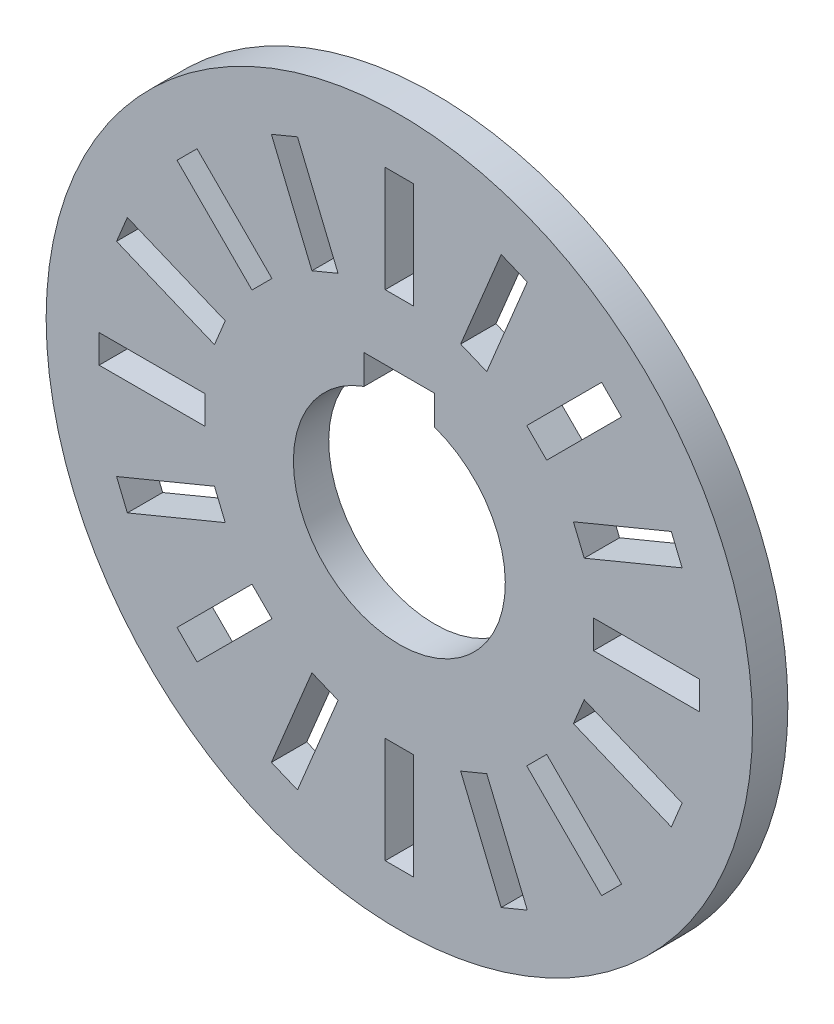
SolidWorks part; units mm, degrees
material "Malleable Cast Iron"
ref_plane "Front Plane" through (0, 0, 0) normal (0, 0, 1) x (1, 0, 0)
ref_plane "Top Plane" through (0, 0, 0) normal (0, 1, 0) x (1, 0, 0)
ref_plane "Right Plane" through (0, 0, 0) normal (1, 0, 0) x (0, 0, -1)
sketch "Sketch1" plane through (0, 0, 0) normal (0, 0, 1) x (1, 0, 0)
  line L0 (-5, 14.1421) -> (-5, 18.3)
  line L1 (5, 18.3) -> (5, 14.1421)
  line L2 (-5, 18.3) -> (5, 18.3)
  line L3 (0, 0) -> (0, 50) construction
  line L4 (-42.5, 2) -> (-27.5, 2)
  line L5 (-42.5, 2) -> (-42.5, -2)
  line L6 (-42.5, -2) -> (-27.5, -2)
  line L7 (-27.5, 2) -> (-27.5, -2)
  line L8 (-42.5, 2) -> (-27.5, -2) construction
  line L9 (-42.5, -2) -> (-27.5, 2) construction
  line L10 (0, 0) -> (19.1342, 46.194) construction
  line L11 (0, 0) -> (35.3553, 35.3553) construction
  line L12 (0, 0) -> (46.194, 19.1342) construction
  line L13 (0, 0) -> (50, 0) construction
  line L14 (0, 0) -> (46.194, -19.1342) construction
  line L15 (0, 0) -> (35.3553, -35.3553) construction
  line L16 (0, 0) -> (19.1342, -46.194) construction
  line L17 (0, 0) -> (0, -50) construction
  line L18 (0, 0) -> (-19.1342, -46.194) construction
  line L19 (0, 0) -> (-35.3553, -35.3553) construction
  line L20 (0, 0) -> (-46.194, -19.1342) construction
  line L21 (0, 0) -> (-50, 0) construction
  line L22 (0, 0) -> (-46.194, 19.1342) construction
  line L23 (0, 0) -> (-35.3553, 35.3553) construction
  line L24 (0, 0) -> (-19.1342, 46.194) construction
  line L25 (-38.4995, 18.1118) -> (-24.6413, 12.3716)
  line L26 (-38.4995, 18.1118) -> (-26.1721, 8.676) construction
  line L27 (-38.4995, 18.1118) -> (-40.0302, 14.4163)
  line L28 (-24.6413, 12.3716) -> (-26.1721, 8.676)
  line L29 (-40.0302, 14.4163) -> (-26.1721, 8.676)
  line L30 (-40.0302, 14.4163) -> (-24.6413, 12.3716) construction
  line L31 (-28.6378, 31.4663) -> (-18.0312, 20.8597)
  line L32 (-28.6378, 31.4663) -> (-20.8597, 18.0312) construction
  line L33 (-28.6378, 31.4663) -> (-31.4663, 28.6378)
  line L34 (-18.0312, 20.8597) -> (-20.8597, 18.0312)
  line L35 (-31.4663, 28.6378) -> (-20.8597, 18.0312)
  line L36 (-31.4663, 28.6378) -> (-18.0312, 20.8597) construction
  line L37 (-14.4163, 40.0302) -> (-8.676, 26.1721)
  line L38 (-14.4163, 40.0302) -> (-12.3716, 24.6413) construction
  line L39 (-14.4163, 40.0302) -> (-18.1118, 38.4995)
  line L40 (-8.676, 26.1721) -> (-12.3716, 24.6413)
  line L41 (-18.1118, 38.4995) -> (-12.3716, 24.6413)
  line L42 (-18.1118, 38.4995) -> (-8.676, 26.1721) construction
  line L43 (2, 42.5) -> (2, 27.5)
  line L44 (2, 42.5) -> (-2, 27.5) construction
  line L45 (2, 42.5) -> (-2, 42.5)
  line L46 (2, 27.5) -> (-2, 27.5)
  line L47 (-2, 42.5) -> (-2, 27.5)
  line L48 (-2, 42.5) -> (2, 27.5) construction
  line L49 (18.1118, 38.4995) -> (12.3716, 24.6413)
  line L50 (18.1118, 38.4995) -> (8.676, 26.1721) construction
  line L51 (18.1118, 38.4995) -> (14.4163, 40.0302)
  line L52 (12.3716, 24.6413) -> (8.676, 26.1721)
  line L53 (14.4163, 40.0302) -> (8.676, 26.1721)
  line L54 (14.4163, 40.0302) -> (12.3716, 24.6413) construction
  line L55 (31.4663, 28.6378) -> (20.8597, 18.0312)
  line L56 (31.4663, 28.6378) -> (18.0312, 20.8597) construction
  line L57 (31.4663, 28.6378) -> (28.6378, 31.4663)
  line L58 (20.8597, 18.0312) -> (18.0312, 20.8597)
  line L59 (28.6378, 31.4663) -> (18.0312, 20.8597)
  line L60 (28.6378, 31.4663) -> (20.8597, 18.0312) construction
  line L61 (40.0302, 14.4163) -> (26.1721, 8.676)
  line L62 (40.0302, 14.4163) -> (24.6413, 12.3716) construction
  line L63 (40.0302, 14.4163) -> (38.4995, 18.1118)
  line L64 (26.1721, 8.676) -> (24.6413, 12.3716)
  line L65 (38.4995, 18.1118) -> (24.6413, 12.3716)
  line L66 (38.4995, 18.1118) -> (26.1721, 8.676) construction
  line L67 (42.5, -2) -> (27.5, -2)
  line L68 (42.5, -2) -> (27.5, 2) construction
  line L69 (42.5, -2) -> (42.5, 2)
  line L70 (27.5, -2) -> (27.5, 2)
  line L71 (42.5, 2) -> (27.5, 2)
  line L72 (42.5, 2) -> (27.5, -2) construction
  line L73 (38.4995, -18.1118) -> (24.6413, -12.3716)
  line L74 (38.4995, -18.1118) -> (26.1721, -8.676) construction
  line L75 (38.4995, -18.1118) -> (40.0302, -14.4163)
  line L76 (24.6413, -12.3716) -> (26.1721, -8.676)
  line L77 (40.0302, -14.4163) -> (26.1721, -8.676)
  line L78 (40.0302, -14.4163) -> (24.6413, -12.3716) construction
  line L79 (28.6378, -31.4663) -> (18.0312, -20.8597)
  line L80 (28.6378, -31.4663) -> (20.8597, -18.0312) construction
  line L81 (28.6378, -31.4663) -> (31.4663, -28.6378)
  line L82 (18.0312, -20.8597) -> (20.8597, -18.0312)
  line L83 (31.4663, -28.6378) -> (20.8597, -18.0312)
  line L84 (31.4663, -28.6378) -> (18.0312, -20.8597) construction
  line L85 (14.4163, -40.0302) -> (8.676, -26.1721)
  line L86 (14.4163, -40.0302) -> (12.3716, -24.6413) construction
  line L87 (14.4163, -40.0302) -> (18.1118, -38.4995)
  line L88 (8.676, -26.1721) -> (12.3716, -24.6413)
  line L89 (18.1118, -38.4995) -> (12.3716, -24.6413)
  line L90 (18.1118, -38.4995) -> (8.676, -26.1721) construction
  line L91 (-2, -42.5) -> (-2, -27.5)
  line L92 (-2, -42.5) -> (2, -27.5) construction
  line L93 (-2, -42.5) -> (2, -42.5)
  line L94 (-2, -27.5) -> (2, -27.5)
  line L95 (2, -42.5) -> (2, -27.5)
  line L96 (2, -42.5) -> (-2, -27.5) construction
  line L97 (-18.1118, -38.4995) -> (-12.3716, -24.6413)
  line L98 (-18.1118, -38.4995) -> (-8.676, -26.1721) construction
  line L99 (-18.1118, -38.4995) -> (-14.4163, -40.0302)
  line L100 (-12.3716, -24.6413) -> (-8.676, -26.1721)
  line L101 (-14.4163, -40.0302) -> (-8.676, -26.1721)
  line L102 (-14.4163, -40.0302) -> (-12.3716, -24.6413) construction
  line L103 (-31.4663, -28.6378) -> (-20.8597, -18.0312)
  line L104 (-31.4663, -28.6378) -> (-18.0312, -20.8597) construction
  line L105 (-31.4663, -28.6378) -> (-28.6378, -31.4663)
  line L106 (-20.8597, -18.0312) -> (-18.0312, -20.8597)
  line L107 (-28.6378, -31.4663) -> (-18.0312, -20.8597)
  line L108 (-28.6378, -31.4663) -> (-20.8597, -18.0312) construction
  line L109 (-40.0302, -14.4163) -> (-26.1721, -8.676)
  line L110 (-40.0302, -14.4163) -> (-24.6413, -12.3716) construction
  line L111 (-40.0302, -14.4163) -> (-38.4995, -18.1118)
  line L112 (-26.1721, -8.676) -> (-24.6413, -12.3716)
  line L113 (-38.4995, -18.1118) -> (-24.6413, -12.3716)
  line L114 (-38.4995, -18.1118) -> (-26.1721, -8.676) construction
  arc A0 (-5, 14.1421) -> (5, 14.1421) centre (0, 0) ccw
  circle A1 centre (0, 0) radius 50
  point P8 (-35, 0)
  point P30 (0, 0)
  point P92 (0, 0)
  dimension "D1" = 15
  dimension "D5" = 100
  dimension "D2" = 10
  dimension "D3" = 18.3
  dimension "D4" = 5
  dimension "D6" = 4
  dimension "D7" = 15
  dimension "D8" = 35
  dimension "D9" = 16
  dimension "D10" = 16
extrude "Boss-Extrude1" add sketch "Sketch1" along normal blind 5 contours A1 L4 L7 L6 L5 L29 L27 L25 L28 L35 L33 L31 L34 L41 L39 L37 L40 L53 L51 L49 L52 L59 L57 L55 L58 L65 L63 L61 L64 L71 L69 L67 L70 L77 L75 L73 L76 L83 L81 L79 L82
